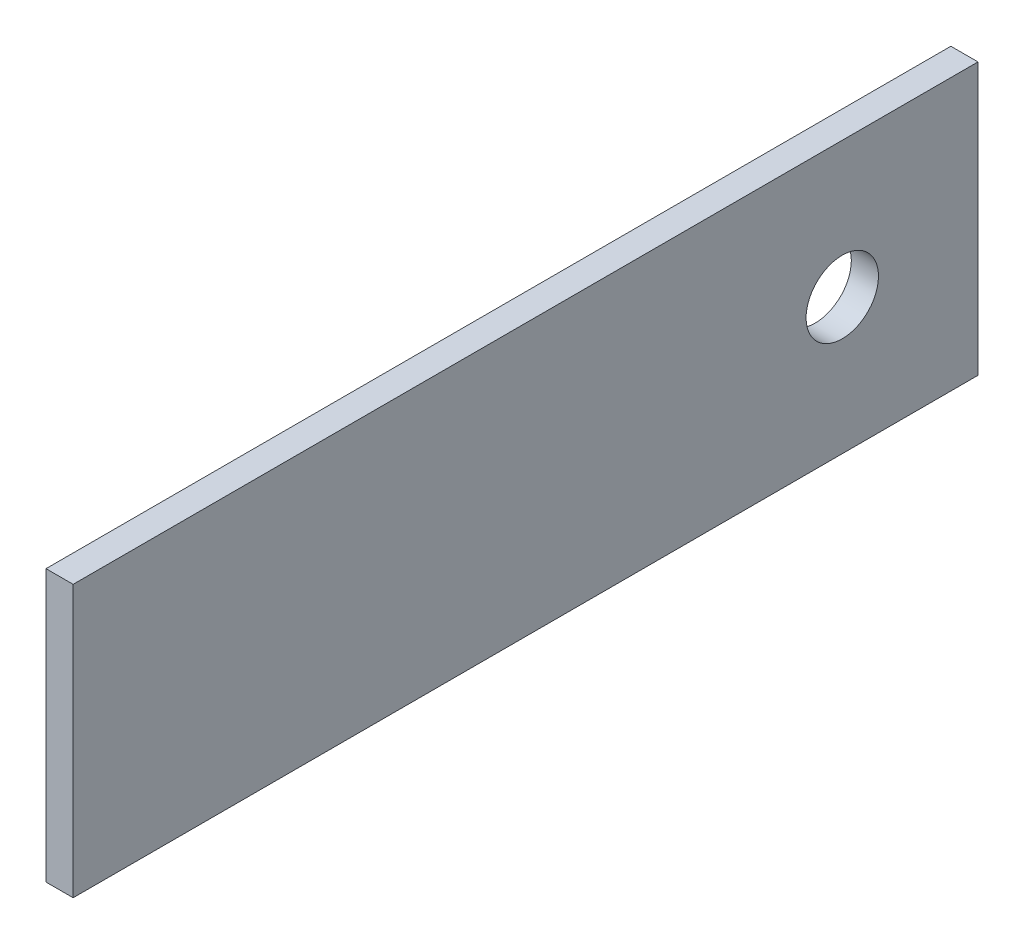
SolidWorks part; units mm, degrees
ref_plane "Front" through (0, 0, 0) normal (0, 0, 1) x (1, 0, 0)
ref_plane "Top" through (0, 0, 0) normal (0, 1, 0) x (1, 0, 0)
ref_plane "Right" through (0, 0, 0) normal (1, 0, 0) x (0, 0, -1)
sketch "Sketch1" plane through (0, 0, 0) normal (0, 0, 1) x (1, 0, 0)
  line L0 (0, 0) -> (0, 30)
  line L1 (0, 30) -> (3, 30)
  line L2 (3, 30) -> (3, 0)
  line L6 (0, 0) -> (3, 0)
  dimension "D1" = 30
  dimension "D2" = 30
  dimension "D3" = 3
extrude "Boss-Extrude1" add sketch "Sketch1" along normal blind 100
sketch "Sketch3" plane through (3, 0, 0) normal (1, 0, 0) x (0, 0, -1)
  line L0 (-100, 30) -> (0, 30) construction
  line L1 (0, 0) -> (0, 30) construction
  circle A0 centre (-15, 15) radius 4
  dimension "D1" = 8
  dimension "D2" = 15
  dimension "D3" = 15
extrude "Cut-Extrude2" cut sketch "Sketch3" against normal blind 10
